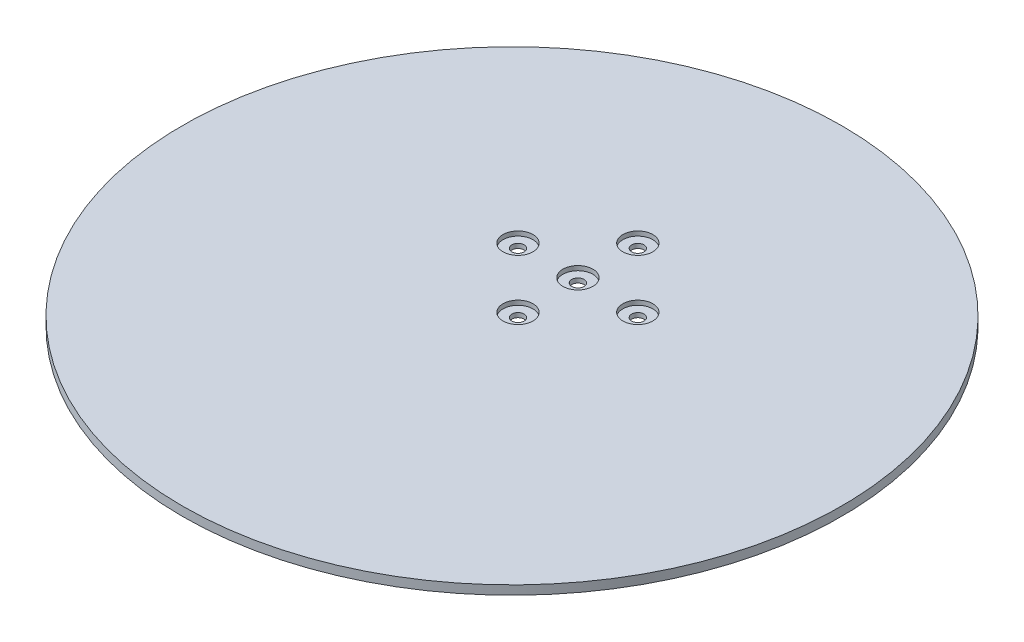
SolidWorks part; units mm, degrees
material "黑玻纤板"
ref_plane "前视基准面" through (0, 0, 0) normal (0, 0, 1) x (1, 0, 0)
ref_plane "上视基准面" through (0, 0, 0) normal (0, 1, 0) x (1, 0, 0)
ref_plane "右视基准面" through (0, 0, 0) normal (1, 0, 0) x (0, 0, -1)
sketch "草图1" plane through (0, 0, 0) normal (0, 1, 0) x (1, 0, 0)
  circle A0 centre (0, 0) radius 110
  dimension "D1" = 220
extrude "凸台-拉伸1" add sketch "草图1" along normal blind 3
sketch "草图2" plane through (0, 3, 0) normal (0, 1, 0) x (1, 0, 0)
  line L0 (0, 110) -> (0, 22) construction
  line L1 (0, 22) -> (107.7775, 22) construction
  circle A0 centre (20, 22) radius 2.05
  circle A1 centre (0, 0) radius 110 construction
  circle A2 centre (0, 22) radius 2.05
  circle A3 centre (0, 42) radius 2.05
  circle A4 centre (0, 2) radius 2.05
  circle A5 centre (-20, 22) radius 2.05
  point P4 (0, 0)
  point P9 (0, 0)
  point P10 (0, 0)
  point P17 (0, 0)
  point P18 (0.0168, 54.0004)
  point P19 (-0.0155, 65.0062)
  point P20 (-10.5389, 77.9091)
  point P21 (12.206, 65.3866)
  point P22 (0, 61.2956)
  point P23 (0, 25.7872)
  point P24 (0, 43.3114)
  point P25 (0, 40.6815)
  point P26 (-18.961, 45.5491)
  point P27 (0, 47.0861)
  dimension "D7" = 22
  dimension "D1" = 4.1
  dimension "D2" = 20
  dimension "D3" = 4
  dimension "D4" = 20
  dimension "D5" = 20
  dimension "D6" = 20
extrude "切除-拉伸1" cut sketch "草图2" against normal through all both and the other way through all
sketch "草图4" plane through (0, 3, 0) normal (0, 1, 0) x (1, 0, 0)
  circle A0 centre (0, 22) radius 5
  circle A1 centre (20, 22) radius 5
  circle A2 centre (0, 42) radius 5
  circle A3 centre (0, 2) radius 5
  circle A4 centre (-20, 22) radius 5
  dimension "D1" = 10
  dimension "D2" = 10
extrude "切除-拉伸2" cut sketch "草图4" against normal blind 1.5
